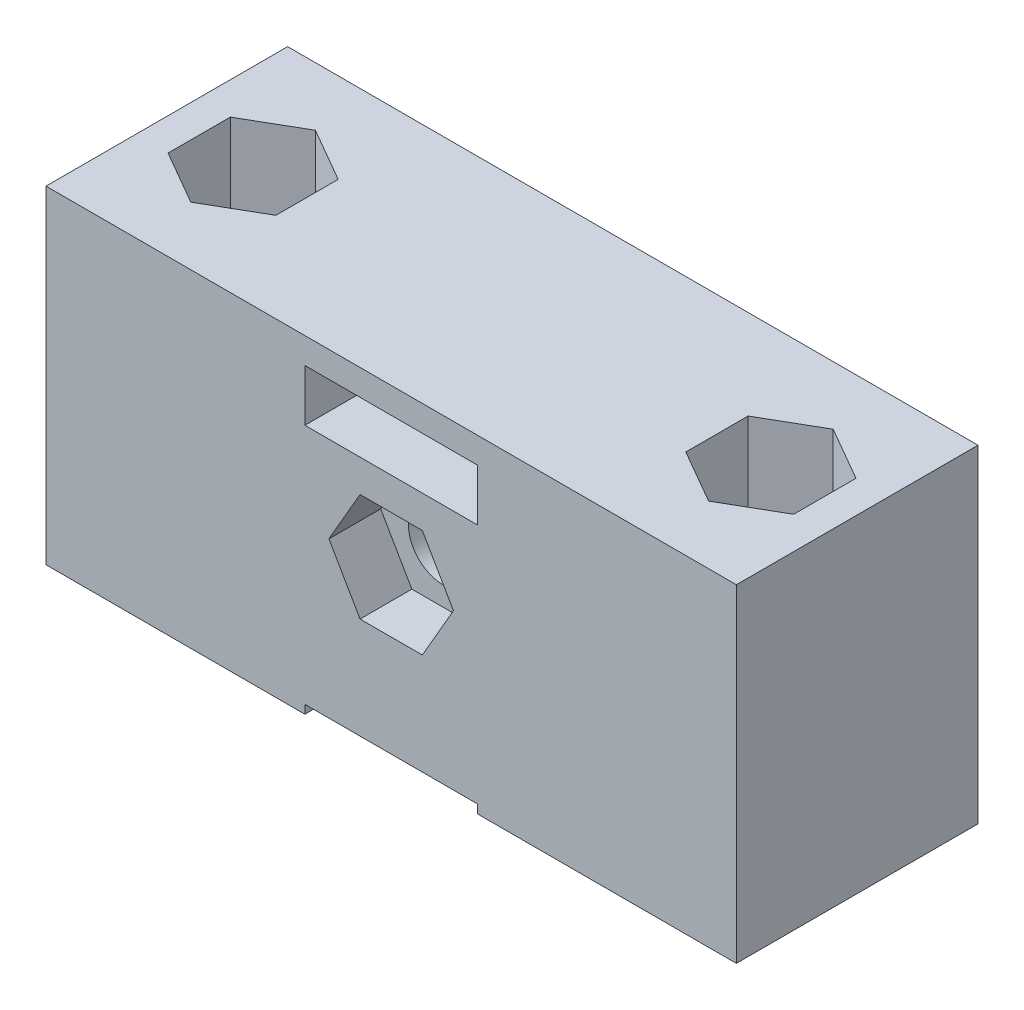
SolidWorks part; units mm, degrees
ref_plane "Front Plane" through (0, 0, 0) normal (0, 0, 1) x (1, 0, 0)
ref_plane "Top Plane" through (0, 0, 0) normal (0, 1, 0) x (1, 0, 0)
ref_plane "Right Plane" through (0, 0, 0) normal (1, 0, 0) x (0, 0, -1)
sketch "Sketch1" plane through (0, 0, 0) normal (0, 1, 0) x (1, 0, 0)
  line L1 (-20, 7) -> (20, 7)
  line L2 (-20, 7) -> (-20, -7)
  line L3 (-20, -7) -> (20, -7)
  line L4 (20, 7) -> (20, -7)
  line L5 (-20, 7) -> (20, -7) construction
  line L6 (-20, -7) -> (20, 7) construction
  point P0 (0, 0)
  dimension "D1" = 40
  dimension "D2" = 14
extrude "Boss-Extrude1" add sketch "Sketch1" along normal blind 19
sketch "Sketch2" plane through (0, 0, 7) normal (0, 0, 1) x (1, 0, 0)
  line L0 (0, 19) -> (0, 0) construction
  line L1 (-20, 19) -> (20, 19) construction
  line L3 (-5, 14.5) -> (5, 14.5)
  line L4 (-5, 14.5) -> (-5, 17.5)
  line L5 (-5, 17.5) -> (5, 17.5)
  line L6 (5, 14.5) -> (5, 17.5)
  line L7 (-5, 14.5) -> (5, 17.5) construction
  line L8 (-5, 17.5) -> (5, 14.5) construction
  line L9 (-5, -0.5) -> (5, -0.5)
  line L10 (-5, -0.5) -> (-5, 0.5)
  line L11 (-5, 0.5) -> (5, 0.5)
  line L12 (5, -0.5) -> (5, 0.5)
  line L13 (-5, -0.5) -> (5, 0.5) construction
  line L14 (-5, 0.5) -> (5, -0.5) construction
  point P5 (0, 16)
  dimension "D1" = 10
  dimension "D2" = 3
  dimension "D3" = 16
  dimension "D4" = 10
  dimension "D5" = 1
extrude "Cut-Extrude1" cut sketch "Sketch2" against normal blind 30
sketch "Sketch3" plane through (0, 0, 7) normal (0, 0, 1) x (1, 0, 0)
  line L0 (0, 19) -> (0, 0) construction
  line L1 (-20, 19) -> (20, 19) construction
  circle A0 centre (0, 9.5) radius 2
  dimension "D1" = 4
extrude "Cut-Extrude2" cut sketch "Sketch3" against normal through all
sketch "Sketch4" plane through (0, 19, 0) normal (0, 1, 0) x (1, 0, 0)
  line L0 (-20, 0) -> (20, 0) construction
  line L1 (-20, 7) -> (-20, -7) construction
  line L2 (20, -7) -> (20, 7) construction
  line L3 (0, 7) -> (0, -7) construction
  line L4 (20, 7) -> (-20, 7) construction
  line L5 (-20, -7) -> (20, -7) construction
  circle A0 centre (-15, 0) radius 1.6
  circle A1 centre (15, 0) radius 1.6
  dimension "D1" = 3.2
  dimension "D2" = 15
extrude "Cut-Extrude3" cut sketch "Sketch4" against normal through all
sketch "Sketch8" plane through (0, 0, 0) normal (0, -1, 0) x (-1, 0, 0)
  line L0 (-5, 7) -> (-5, -7) construction
  line L1 (5, -7) -> (-5, -7)
  line L2 (5, -7) -> (5, -6)
  line L3 (5, -6) -> (-5, -6)
  line L4 (-5, -7) -> (-5, -6)
  dimension "D1" = 1
extrude "Boss-Extrude2" [suppressed] add sketch "Sketch8" against normal up to next
sketch "Sketch9" plane through (0, 19, 0) normal (0, 1, 0) x (1, 0, 0)
  line L0 (0, 7) -> (0, -7) construction
  line L1 (-15, 3.6084) -> (-18.125, 1.8042)
  line L2 (-18.125, 1.8042) -> (-18.125, -1.8042)
  line L3 (-18.125, -1.8042) -> (-15, -3.6084)
  line L4 (-15, -3.6084) -> (-11.875, -1.8042)
  line L5 (-11.875, -1.8042) -> (-11.875, 1.8042)
  line L6 (-11.875, 1.8042) -> (-15, 3.6084)
  line L7 (20, 7) -> (-20, 7) construction
  line L8 (-20, -7) -> (20, -7) construction
  line L9 (11.875, 1.8042) -> (15, 3.6084)
  line L10 (11.875, -1.8042) -> (11.875, 1.8042)
  line L11 (15, -3.6084) -> (11.875, -1.8042)
  line L12 (18.125, -1.8042) -> (15, -3.6084)
  line L13 (18.125, 1.8042) -> (18.125, -1.8042)
  line L14 (15, 3.6084) -> (18.125, 1.8042)
  circle A0 centre (-15, 0) radius 3.125 construction
  circle A1 centre (15, 0) radius 3.125 construction
  dimension "D1" = 6.25
extrude "Cut-Extrude4" cut sketch "Sketch9" against normal blind 10
sketch "Sketch10" plane through (0, 0, 7) normal (0, 0, 1) x (1, 0, 0)
  line L1 (1.8042, 12.625) -> (-1.8042, 12.625)
  line L2 (-1.8042, 12.625) -> (-3.6084, 9.5)
  line L3 (-3.6084, 9.5) -> (-1.8042, 6.375)
  line L4 (-1.8042, 6.375) -> (1.8042, 6.375)
  line L5 (1.8042, 6.375) -> (3.6084, 9.5)
  line L6 (3.6084, 9.5) -> (1.8042, 12.625)
  circle A0 centre (0, 9.5) radius 3.125 construction
  dimension "D1" = 6.25
extrude "Cut-Extrude5" cut sketch "Sketch10" against normal blind 3
equation "\"X-ROD-SPACING\"=45"
equation "\"Y-ROD-SPACING\"=75"
equation "\"Z-ROD-SPACING\"=17.5"
equation "\"Y-BED-OFFSET\"=2"
equation "\"Y-BED-ROD-INSET\"=3.5"
equation "\"Y-BED-SCREW-SPACING\"=209"
equation "\"Y-BED-SCREW-CUTOUT-SLOT-HEIGHT\"=2"
equation "\"T-SLOT-NUT-FILLET-RADIUS\"=0.25"
equation "\"T-SLOT-SCREW-SHAFT-RADIUS\"=1.75"
equation "\"T-SLOT-SCREW-SHAFT-CUTOUT-LENGTH\"=10.5"
equation "\"T-SLOT-NUT-DEPTH\"=4.2"
equation "\"T-SLOT-NUT-WIDTH\"=3"
equation "\"T-SLOT-NUT-END-DISTANCE\"=8"
equation "\"ACRYLIC-THICKNESS\"=10"
equation "\"ACRYLIC-THICKNESS2\"=4.5"
equation "\"ACRYLIC-TAB-CUTOUT-SIZE\"=\"ACRYLIC-THICKNESS\"+\"ACRYLIC-TAB-TOLERANCE\"*2"
equation "\"ACRYLIC-TAB-TOLERANCE\"=.1"
equation "\"ACRYLIC-TAB-WIDTH\"=\"ACRYLIC-THICKNESS\""
equation "\"ACRYLIC-M3-HOLE\"=3.1"
equation "\"SMOOTHROD-CAP-SCREW-DISTANCE\"=20"
equation "\"FRAME-WIDTH-INNER\"=370"
equation "\"NEMA17-HOLE-SPACING\"=31"
equation "\"NEMA17-CENTRAL-CUTOUT\"=22.5"
equation "\"Z-BRACKET-REACH\"=55"
equation "\"Z-ROD-INSET\"=16"
equation "\"TOP-BRACKET-SPACING\"=40"
equation "\"SMOOTHROD-X-LENGTH\"=350"
equation "\"SMOOTHROD-Y-LENGTH\"=350"
equation "\"SMOOTHROD-Z-LENGTH\"=350"
equation "\"SMOOTHROD-TIGHTENING-HEADROOM\"=.25"
equation "\"LEADSCREW-Z-LENGTH\"=300"
equation "\"SCREW-LENGTH-FRAME\"=\"ACRYLIC-THICKNESS\" + 10"
equation "\"SCREW-LENGTH-MOTOR\"=\"ACRYLIC-THICKNESS\" + 5"
equation "\"SCREW-LENGTH-EXTRUDER\"=28"
equation "\"SCREW-HEAD-RADIUS\"=6"
equation "\"PRINTED-M3-HOLE\"=3.5"
equation "\"PRINTED-X-SMOOTHROD-DIAMETER\"=8.2"
equation "\"PRINTED-X-SMOOTHROD-CUTOUT\"=10"
equation "\"PRINTED-X-BASE-HEIGHT\"=10"
equation "\"PRINTED-LM8UU-CUTOUT-SIZE\"=15.25"
equation "\"PRINTED-LM8UU-CUTOUT-LENGTH\"=24.5"
equation "\"PRINTED-X-IDLER-HEIGHT\"=16"
equation "\"PSU-MOUNTING-WIDTH\"=95"
equation "\"PSU-MOUNTING-HEIGHT\"=177"
equation "\"Y-BELT-TO-ROD-DISTANCE\"=20"
equation "\"SPOOL-HOLDER-ROD-SPACING\"=150"
equation "\"ACRYLIC-X-CARRIAGE-WIDTH\"=55"
equation "\"ACRYLIC-X-CARRIAGE-HEIGHT\"=75"
equation "\"ACRYLIC-X-CARRIAGE-LM8UU-CUTOUT-WIDTH\"=24.25"
equation "\"ACRYLIC-X-CARRIAGE-LM8UU-CUTOUT-HEIGHT\"=11.5"
equation "\"ACRYLIC-X-CARRIAGE-SCREW-SPACING-X\"=15"
equation "\"ACRYLIC-X-CARRIAGE-SCREW-SPACING-Y\"=33"
equation "\"ACRYLIC-X-CARRIAGE-CENTER-TAB-SPACING\"=14"
equation "\"ACRYLIC-X-CARRIAGE-EXTRUDER-OFFSET\"=26"
equation "\"ACRYLIC-X-CARRIAGE-EXTRUDER-ANGLE\"=90"
equation "\"ACRYLIC-X-CARRIAGE-EXTRUDER-SHELF-DEPTH\"=\"ACRYLIC-X-CARRIAGE-EXTRUDER-OFFSET\" + 28"
equation "\"ACRYLIC-X-CARRIAGE-EXTRUDER-BRACE-SPACING\"=23"
equation "\"ACRYLIC-X-CARRIAGE-EXTRUDER-BRACE-TAB-OFFSET\"=20"
equation "\"ACRYLIC-X-CARRIAGE-EXTRUDER-BRACE-HEIGHT\"=35"
equation "\"ACRYLIC-X-CARRIAGE-EXTRUDER-BRACE-SCREW-SPACING\"=22"
equation "\"ACRYLIC-X-CARRIAGE-DUAL-WIDTH-MULTIPLIER\"=1.65"
equation "\"ACRYLIC-X-CARRIAGE-DUAL-HOTEND-SPACING\"=42"
equation "\"ACRYLIC-X-CARRIAGE-DUAL-WIDTH\"=103"
equation "\"ACRYLIC-X-CARRIAGE-DUAL-HOTEND-SEPARATION\"=35"
equation "\"ACRYLIC-X-CARRIAGE-DUAL-MOUNT-PLATE-DEPTH\"=76"
equation "\"ACRYLIC-X-CARRIAGE-DUAL-MOUNT-BRACE-WIDTH\"=45"
equation "\"ACRYLIC-X-CARRIAGE-DUAL-MOUNT-SCREW-WIDTH\"=40"
equation "\"BLOWER-FAN-WIDTH\"=15"
equation "\"PRINTED-M3-NUT-AF\"=6.25"
equation "\"D1@Sketch9\"=\"PRINTED-M3-NUT-AF\""
equation "\"D1@Sketch10\"=\"PRINTED-M3-NUT-AF\""
